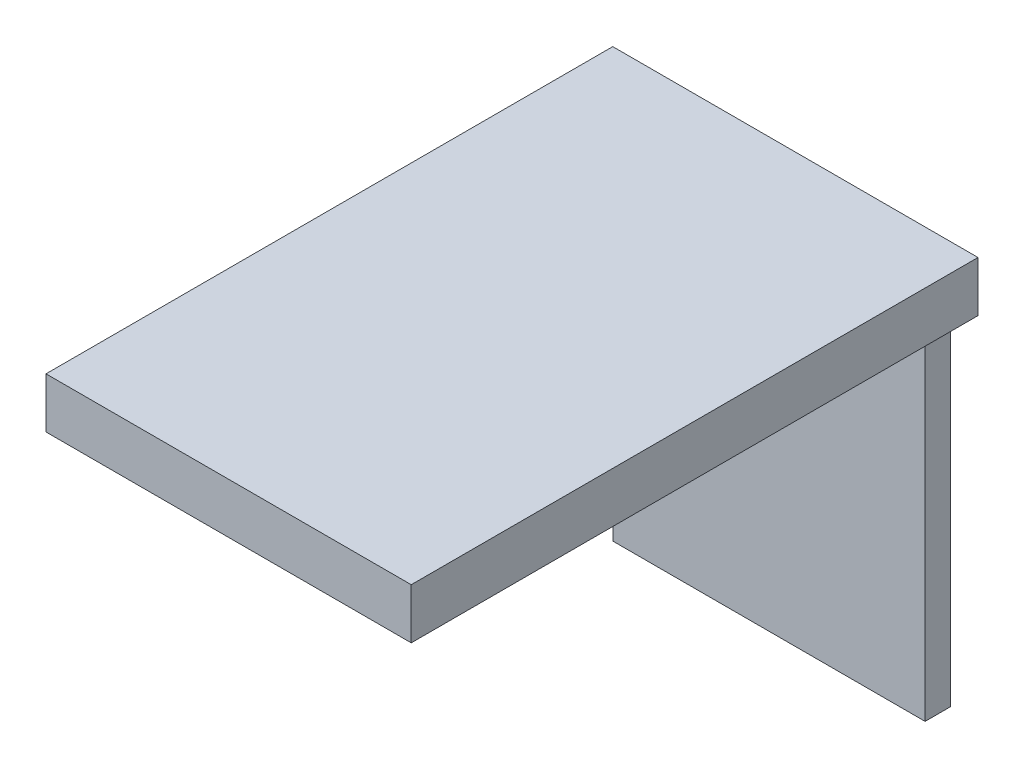
SolidWorks part; units mm, degrees
ref_plane "Front Plane" through (0, 0, 0) normal (0, 0, 1) x (1, 0, 0)
ref_plane "Top Plane" through (0, 0, 0) normal (0, 1, 0) x (1, 0, 0)
ref_plane "Right Plane" through (0, 0, 0) normal (1, 0, 0) x (0, 0, -1)
sketch "Sketch1" plane through (0, 0, 0) normal (0, 1, 0) x (1, 0, 0)
  line L1 (-14.5, 22.5) -> (14.5, 22.5)
  line L2 (-14.5, 22.5) -> (-14.5, -22.5)
  line L3 (-14.5, -22.5) -> (14.5, -22.5)
  line L4 (14.5, 22.5) -> (14.5, -22.5)
  line L5 (-14.5, 22.5) -> (14.5, -22.5) construction
  line L6 (-14.5, -22.5) -> (14.5, 22.5) construction
  line L7 (-12.5, 20.5) -> (12.5, 20.5)
  line L8 (-12.5, 20.5) -> (-12.5, -20.5)
  line L9 (-12.5, -20.5) -> (12.5, -20.5)
  line L10 (12.5, 20.5) -> (12.5, -20.5)
  line L11 (-12.5, 20.5) -> (12.5, -20.5) construction
  line L12 (-12.5, -20.5) -> (12.5, 20.5) construction
  point P0 (0, 0)
  point P6 (0, 0)
  dimension "D1" = 45
  dimension "D2" = 29
  dimension "D3" = 2
  dimension "D4" = 2
extrude "Boss-Extrude1" add sketch "Sketch1" along normal blind 3
sketch "Sketch2" plane through (0, 3, 0) normal (0, 1, 0) x (1, 0, 0)
  line L1 (-14.5, 22.5) -> (14.5, 22.5)
  line L2 (-14.5, 22.5) -> (-14.5, -22.5)
  line L3 (-14.5, -22.5) -> (14.5, -22.5)
  line L4 (14.5, 22.5) -> (14.5, -22.5)
  line L5 (-14.5, 22.5) -> (14.5, -22.5) construction
  line L6 (-14.5, -22.5) -> (14.5, 22.5) construction
  point P0 (0, 0)
extrude "Boss-Extrude2" add sketch "Sketch2" along normal blind 1
sketch "Sketch4" plane through (0, 0, 0) normal (0, -1, 0) x (-1, 0, 0)
  line L1 (-14.5, 22.5) -> (14.5, 22.5) construction
  line L2 (12.5, 20.5) -> (-12.3, 20.5)
  line L3 (12.5, 20.5) -> (12.5, 22.5)
  line L4 (12.5, 22.5) -> (-12.3, 22.5)
  line L5 (-12.3, 20.5) -> (-12.3, 22.5)
  line L6 (-14.5, -22.5) -> (-14.5, 22.5) construction
  dimension "D1" = 2.2
extrude "Boss-Extrude3" add sketch "Sketch4" along normal blind 28
